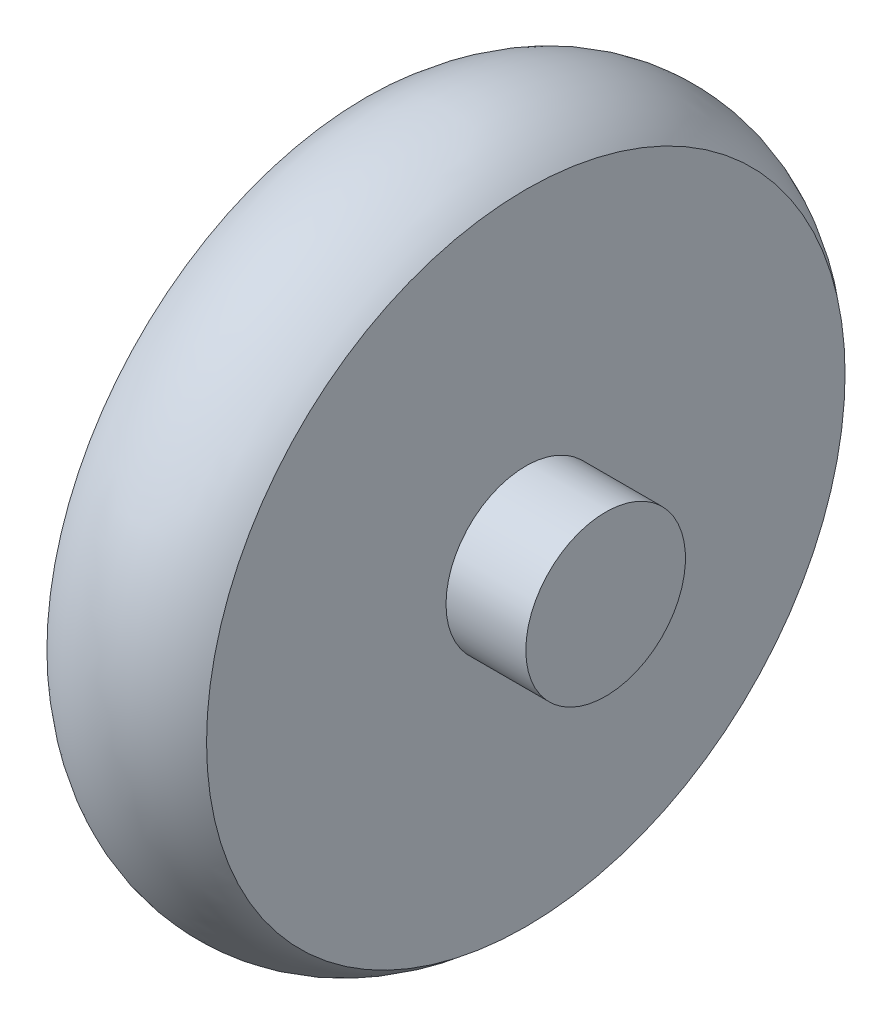
SolidWorks part; units mm, degrees
ref_plane "前视基准面" through (0, 0, 0) normal (0, 0, 1) x (1, 0, 0)
ref_plane "上视基准面" through (0, 0, 0) normal (0, 1, 0) x (1, 0, 0)
ref_plane "右视基准面" through (0, 0, 0) normal (1, 0, 0) x (0, 0, -1)
sketch "草图1" plane through (0, 0, 0) normal (0, 0, 1) x (1, 0, 0)
  line L0 (20, 0) -> (30, 0)
  line L1 (0, 0) -> (20, 0)
  line L2 (0, 10) -> (0, 40)
  line L4 (20, 10) -> (20, 40)
  line L5 (30, 0) -> (30, 10)
  line L7 (0, 0) -> (-10, 0)
  line L8 (-10, 0) -> (-10, 10)
  line L9 (-10, 10) -> (0, 10)
  line L10 (30, 10) -> (20, 10)
  arc A0 (20, 40) -> (0, 40) centre (10, 28.8197) ccw
revolve "旋转1" add sketch "草图1" angle 360 about L1
